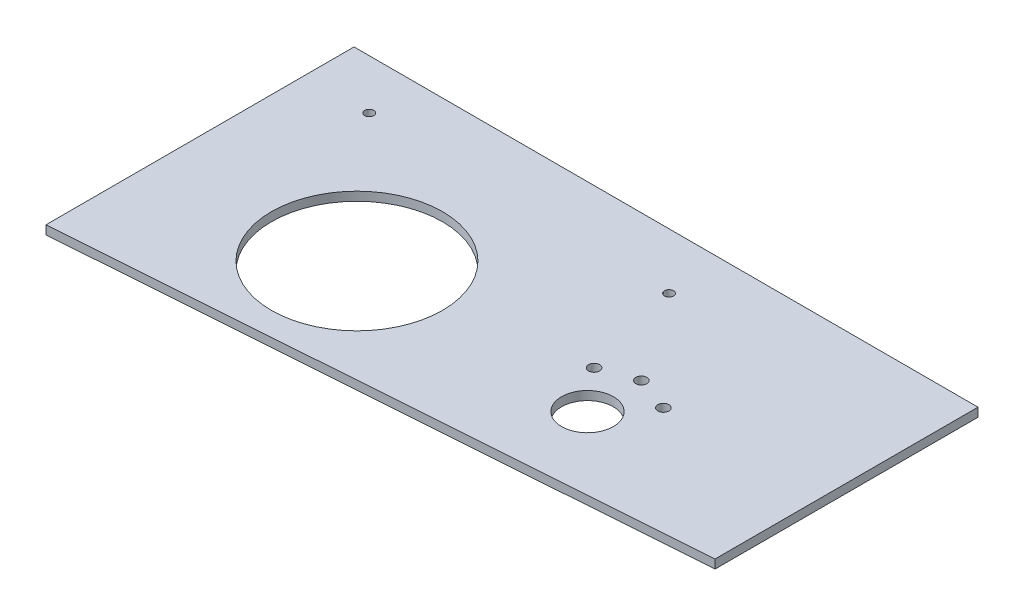
SolidWorks part; units mm, degrees
material "6061-T6 (SS)"
ref_plane "X-Y Datum" through (0, 0, 0) normal (0, 0, 1) x (1, 0, 0)
ref_plane "X-Z Datum" through (0, 0, 0) normal (0, 1, 0) x (1, 0, 0)
ref_plane "Y-Z Datum" through (0, 0, 0) normal (1, 0, 0) x (0, 0, -1)
sketch "Master sketch" plane through (0, 0, 0) normal (0, 1, 0) x (1, 0, 0)
  line L0 (-642.62, -165.1) -> (-642.62, 0) construction
  line L1 (-642.62, 0) -> (-530.86, 0) construction
  line L2 (-414.02, 0) -> (0, 0) construction
  line L3 (-530.86, 0) -> (-414.02, 0) construction
  line L4 (-530.86, 0) -> (-530.86, -114.3) construction
  line L5 (-530.86, -114.3) -> (-537.21, -103.3015) construction
  line L6 (-359.41, 0) -> (-359.41, -127) construction
  circle A0 centre (-642.62, -165.1) radius 12.7 construction
  circle A1 centre (-642.62, 0) radius 12.7 construction
  circle A4 centre (-414.02, 0) radius 12.7 construction
  circle A5 centre (0, 0) radius 12.7 construction
  circle A6 centre (-537.21, -103.3015) radius 78.9148 construction
  circle A7 centre (-359.41, -127) radius 24.535 construction
  circle A8 centre (-642.6321, 0.0082) radius 12.7 construction
  circle A9 centre (-414.0321, 0.0082) radius 12.7 construction
  circle A10 centre (-537.2221, -115.9932) radius 61.9125 construction
  circle A11 centre (-359.4221, -126.9918) radius 18.75 construction
  circle A12 centre (-359.4221, -126.9918) radius 11.25 construction
  point P24 (0, 0)
  dimension "D2" = 25.4
  dimension "D3" = 111.76
  dimension "D11" = 157.8295
  dimension "D12" = 49.07
  dimension "D1" = 165.1
  dimension "D4" = 228.6
  dimension "D5" = 642.62
  dimension "D6" = 114.3
  dimension "D7" = 12.7
  dimension "D8" = 120
  dimension "D9" = 171.45
  dimension "D10" = 127
sketch "Sketch2" plane through (0, 0, 0) normal (0, 1, 0) x (1, 0, 0)
  line L4 (-672.3917, 17.123) -> (-672.3917, -205.8085)
  line L5 (-672.3917, -205.8085) -> (-220.8488, -173.1498)
  line L6 (-220.8488, -173.1498) -> (-220.8488, 17.123)
  line L7 (-220.8488, 17.123) -> (-672.3917, 17.123)
extrude "Boss-Extrude2" add sketch "Sketch2" along normal blind 6.35
sketch "Sketch3" plane through (0, 6.35, 0) normal (0, 1, 0) x (1, 0, 0)
  circle A11 centre (-537.1635, -115.9991) radius 61.9125 construction
  circle A12 centre (-359.3635, -126.9977) radius 18.75 construction
  circle A14 centre (-403.9398, -23.3319) radius 3.3
  circle A15 centre (-625.4917, -18.7958) radius 3.3
  circle A16 centre (-359.3635, -87.9977) radius 4
  circle A17 centre (-384.4323, -97.1219) radius 4
  circle A18 centre (-334.2948, -97.1219) radius 4
  circle A19 centre (-537.1635, -115.9991) radius 61.9125
  circle A20 centre (-359.3635, -126.9977) radius 18.75
extrude "Cut-Extrude1" cut sketch "Sketch3" against normal through all
ref_point "Point1"
ref_point "Point2"
